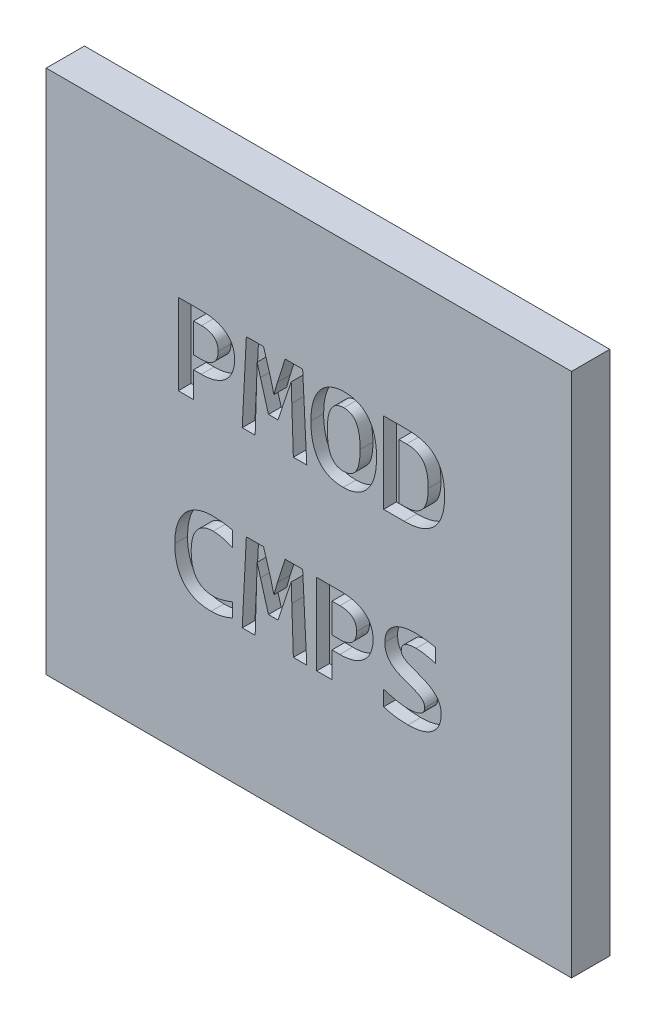
SolidWorks part; units mm, degrees
ref_plane "Front Plane" through (0, 0, 0) normal (0, 0, 1) x (1, 0, 0)
ref_plane "Top Plane" through (0, 0, 0) normal (0, 1, 0) x (1, 0, 0)
ref_plane "Right Plane" through (0, 0, 0) normal (1, 0, 0) x (0, 0, -1)
sketch "Sketch1" plane through (0, 0, 0) normal (0, 0, 1) x (1, 0, 0)
  line L1 (-10.3, -10.3) -> (10.3, -10.3)
  line L2 (-10.3, -10.3) -> (-10.3, 10.3)
  line L3 (-10.3, 10.3) -> (10.3, 10.3)
  line L4 (10.3, -10.3) -> (10.3, 10.3)
  line L5 (-10.3, -10.3) -> (10.3, 10.3) construction
  line L6 (-10.3, 10.3) -> (10.3, -10.3) construction
  point P0 (0, 0)
  dimension "D1" = 20.6
extrude "Boss-Extrude1" add sketch "Sketch1" along normal blind 1.5
sketch "Sketch2" plane through (0, 0, 1.5) normal (0, 0, 1) x (1, 0, 0)
  text T0 "PMOD\r\nCMPS" font "Consolas" height 3.175
extrude "Cut-Extrude1" cut sketch "Sketch2" against normal blind 0.5
